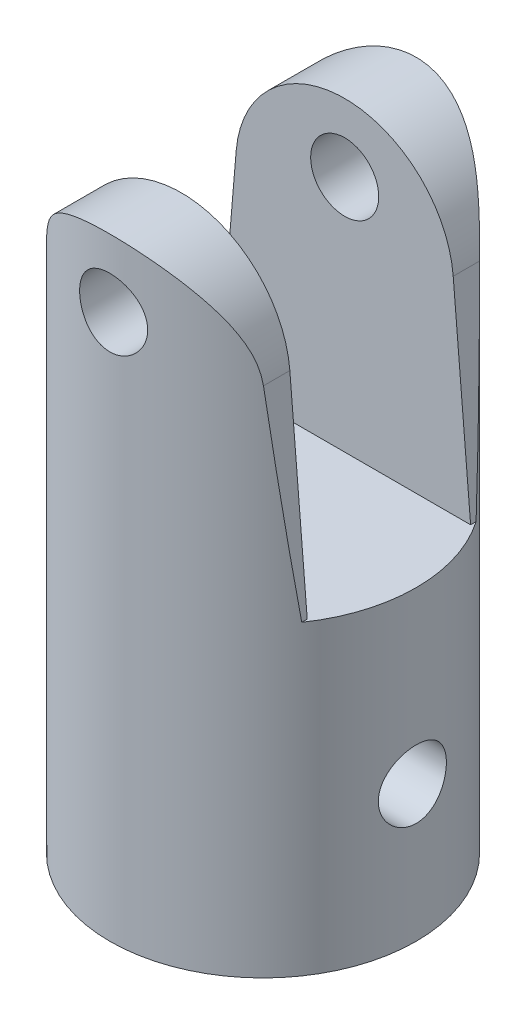
SolidWorks part; units mm, degrees
ref_plane "Front Plane" through (0, 0, 0) normal (0, 0, 1) x (1, 0, 0)
ref_plane "Top Plane" through (0, 0, 0) normal (0, 1, 0) x (1, 0, 0)
ref_plane "Right Plane" through (0, 0, 0) normal (1, 0, 0) x (0, 0, -1)
sketch "Sketch1" plane through (0, 0, 0) normal (0, 1, 0) x (1, 0, 0)
  circle A0 centre (0, 0) radius 7.1438
  dimension "D1" = 14.2875
extrude "Boss-Extrude1" add sketch "Sketch1" along normal mid plane 28.575
sketch "Sketch2" plane through (0, -14.2875, 0) normal (0, -1, 0) x (1, 0, 0)
  circle A0 centre (0, 0) radius 3.175
  dimension "D1" = 6.35
extrude "Cut-Extrude1" cut sketch "Sketch2" against normal blind 12.7
sketch "Sketch3" plane through (0, 14.2875, 0) normal (0, 1, 0) x (1, 0, 0)
  line L1 (-7.1438, -3.81) -> (7.1438, -3.81)
  line L2 (-7.1438, -3.81) -> (-7.1438, 3.81)
  line L3 (-7.1438, 3.81) -> (7.1438, 3.81)
  line L4 (7.1438, -3.81) -> (7.1438, 3.81)
  line L5 (-7.1438, -3.81) -> (7.1438, 3.81) construction
  line L6 (-7.1438, 3.81) -> (7.1438, -3.81) construction
  circle A0 centre (0, 0) radius 7.1438 construction
  point P0 (0, 0)
  dimension "D1" = 7.62
extrude "Cut-Extrude2" cut sketch "Sketch3" against normal offset from surface (14.2875 mm away) 14.2875 up to face at (0, -14.2875, -3.175)
sketch "Sketch4" plane through (0, 0, 0) normal (0, 0, 1) x (1, 0, 0)
  line L0 (-7.1438, 0) -> (-5.8738, 0)
  line L1 (-5.8738, 0) -> (-5.0621, 9.634)
  line L2 (7.1438, 0) -> (5.8738, 0)
  line L3 (7.1438, -14.2875) -> (7.1438, 0) construction
  line L4 (5.8738, 0) -> (5.0621, 9.634)
  line L5 (0, 14.2875) -> (0, -14.2875) construction
  line L6 (6.0429, 14.2875) -> (-6.0429, 14.2875) construction
  line L7 (-7.1438, -14.2875) -> (7.1438, -14.2875) construction
  arc A0 (-5.0621, 9.634) -> (5.0621, 9.634) centre (0, 9.2075) cw
  dimension "D2" = 5.08
  dimension "D1" = 1.27
extrude "Cut-Extrude4" cut sketch "Sketch4" against normal through all both and the other way through all flip side to cut
sketch "Sketch5" plane through (0, 0, 0) normal (0, 0, 1) x (1, 0, 0)
  circle A0 centre (0, 11.1125) radius 1.5875
  dimension "D1" = 3.175
  dimension "D2" = 11.1125
extrude "Cut-Extrude5" cut sketch "Sketch5" against normal through all both and the other way through all
sketch "Sketch6" plane through (0, 0, 0) normal (1, 0, 0) x (0, 0, -1)
  circle A0 centre (0, -7.9375) radius 1.5875
  dimension "D1" = 3.175
  dimension "D2" = 7.9375
extrude "Cut-Extrude6" cut sketch "Sketch6" against normal mid plane 25.4
